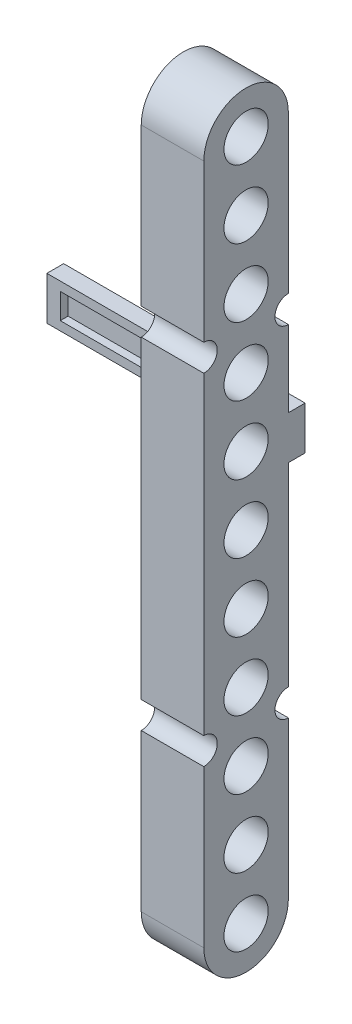
SolidWorks part; units mm, degrees
material "ABS"
ref_plane "Спереди" through (0, 0, 0) normal (0, 0, 1) x (1, 0, 0)
ref_plane "Сверху" through (0, 0, 0) normal (0, 1, 0) x (1, 0, 0)
ref_plane "Справа" through (0, 0, 0) normal (1, 0, 0) x (0, 0, -1)
sketch "Эскиз1" plane through (0, 0, 0) normal (1, 0, 0) x (0, 0, -1)
  line L0 (6.45, -7.6185) -> (6.45, 7.6185)
  line L1 (-6.45, 7.6185) -> (-6.45, -7.6185)
  line L2 (6.45, 7.6185) -> (6.45, 22.8556)
  line L3 (-6.45, 22.8556) -> (-6.45, 7.6185)
  line L4 (6.45, 22.8556) -> (6.45, 38.0926)
  line L5 (-6.45, 38.0926) -> (-6.45, 22.8556)
  line L6 (6.45, 38.0926) -> (6.45, 53.3296)
  line L7 (-6.45, 53.3296) -> (-6.45, 38.0926)
  circle A0 centre (0, 7.6185) radius 4.95
  circle A1 centre (0, -7.6185) radius 4.95
  arc A2 (-6.45, -7.6185) -> (6.45, -7.6185) centre (0, -7.6185) ccw
  circle A4 centre (0, 22.8556) radius 4.95
  circle A5 centre (0, 7.6185) radius 4.95
  circle A8 centre (0, 38.0926) radius 4.95
  circle A9 centre (0, 22.8556) radius 4.95
  circle A12 centre (0, 53.3296) radius 4.95
  circle A13 centre (0, 38.0926) radius 4.95
  arc A15 (6.45, 53.3296) -> (-6.45, 53.3296) centre (0, 53.3296) ccw
extrude "Бобышка-Вытянуть1" add sketch "Эскиз1" along normal blind 14 contours L6 A15 L7 L5 L3 L1 A2 L0 L2 L4 A0 A1 A4 A8 A12
sketch "Эскиз3" plane through (0, 0, -6.45) normal (0, 0, -1) x (-1, 0, 0)
  line L1 (-14, 53.3296) -> (0, 53.3296)
  line L2 (-14, 53.3296) -> (-14, -7.6185)
  line L3 (-14, -7.6185) -> (0, -7.6185)
  line L4 (0, 53.3296) -> (0, -7.6185)
extrude "Бобышка-Вытянуть2" add sketch "Эскиз3" along normal blind 3
sketch "Эскиз4" plane through (0, 0, 0) normal (-1, 0, 0) x (0, 0, 1)
  line L5 (-9.45, 53.3296) -> (-9.45, 57.9482)
  line L6 (0, 63.6167) -> (0, 58.2796) construction
  line L7 (-9.45, 53.3296) -> (-9.45, -12.237)
  line L8 (9.45, 60.9482) -> (-9.45, 60.9482) construction
  line L9 (9.45, -53.3296) -> (9.45, -18.237)
  line L10 (-9.45, 63.9482) -> (-9.45, 99.0408)
  line L11 (9.45, 63.9482) -> (9.45, 99.0408)
  line L12 (0, -12.5685) -> (0, -17.9056) construction
  line L13 (9.45, -15.237) -> (-9.45, -15.237) construction
  line L14 (-9.45, -18.237) -> (-9.45, -53.3296)
  line L15 (9.45, -12.237) -> (9.45, 57.9482)
  circle A0 centre (0, 99.0408) radius 4.95
  circle A2 centre (0, 83.8037) radius 4.95
  circle A3 centre (0, 68.5667) radius 4.95
  circle A4 centre (0, 53.3296) radius 4.95
  circle A5 centre (0, 53.3296) radius 4.95 construction
  circle A6 centre (0, -53.3296) radius 4.95
  circle A8 centre (0, -38.0926) radius 4.95
  circle A9 centre (0, -22.8556) radius 4.95
  circle A10 centre (0, -7.6185) radius 4.95
  circle A11 centre (0, -7.6185) radius 4.95 construction
  arc A13 (-9.45, -53.3296) -> (9.45, -53.3296) centre (0, -53.3296) ccw
  arc A14 (9.45, 99.0408) -> (-9.45, 99.0408) centre (0, 99.0408) ccw
  circle A15 centre (0, 38.0926) radius 4.95
  circle A16 centre (0, 22.8556) radius 4.95
  circle A17 centre (0, 7.6185) radius 4.95
  arc A18 (-9.45, 57.9482) -> (-9.45, 63.9482) centre (-9.45, 60.9482) ccw
  arc A19 (9.45, 63.9482) -> (9.45, 57.9482) centre (9.45, 60.9482) ccw
  arc A20 (-9.45, -18.237) -> (-9.45, -12.237) centre (-9.45, -15.237) ccw
  arc A21 (9.45, -12.237) -> (9.45, -18.237) centre (9.45, -15.237) ccw
  point P48 (0, 60.9482)
  point P61 (0, -15.237)
extrude "Бобышка-Вытянуть3" add sketch "Эскиз4" against normal up to surface (14 mm away) up to face at (14, 7.6185, -4.95)
sketch "Эскиз5" plane through (0, 0, -9.45) normal (0, 0, -1) x (-1, 0, 0)
  line L1 (37, 33.1854) -> (-12, 33.1854)
  line L2 (37, 33.1854) -> (37, 38.8554)
  line L3 (37, 38.8554) -> (-12, 38.8554)
  line L4 (-14, 31.1854) -> (-14, 40.8554)
  line L5 (20.2177, 38.8554) -> (13.8052, 38.8554) construction
  line L6 (39, 40.8554) -> (-14, 40.8554)
  line L8 (39, 31.1854) -> (-14, 31.1854)
  line L10 (-12, 33.1854) -> (-12, 38.8554)
  line L11 (-12, 33.1854) -> (-12, 38.8554) construction
  line L12 (-14, 33.1854) -> (-14, 38.8554) construction
  line L13 (39, 31.1854) -> (-16, 31.1854) construction
  line L14 (-16, 31.1854) -> (-16, 40.8554) construction
  line L15 (39, 40.8554) -> (-16, 40.8554) construction
  line L16 (37, 33.1854) -> (-14, 33.1854) construction
  line L17 (37, 38.8554) -> (-14, 38.8554) construction
  line L19 (39, 31.1854) -> (40, 31.1854)
  line L21 (39, 40.8554) -> (40, 40.8554)
  line L22 (40, 31.1854) -> (40, 40.8554)
  line L23 (39, 31.1854) -> (39, 40.8554) construction
  dimension "D1" = 2
  dimension "D2" = 2
extrude "Бобышка-Вытянуть4" add sketch "Эскиз5" along normal up to surface (1.75 mm away)
sketch "Эскиз6" plane through (0, 0, -11.2) normal (0, 0, -1) x (-1, 0, 0)
  line L1 (39, 31.1854) -> (-14, 31.1854)
  line L3 (39, 40.8554) -> (-14, 40.8554)
  line L4 (-14, 31.1854) -> (-14, 40.8554)
  line L5 (-14, 31.1854) -> (40, 31.1854) construction
  line L6 (-14, 40.8554) -> (-14, 31.1854) construction
  line L8 (39, 31.1854) -> (40, 31.1854)
  line L10 (39, 40.8554) -> (40, 40.8554)
  line L11 (40, 31.1854) -> (40, 40.8554)
extrude "Бобышка-Вытянуть5" add sketch "Эскиз6" along normal blind 2
